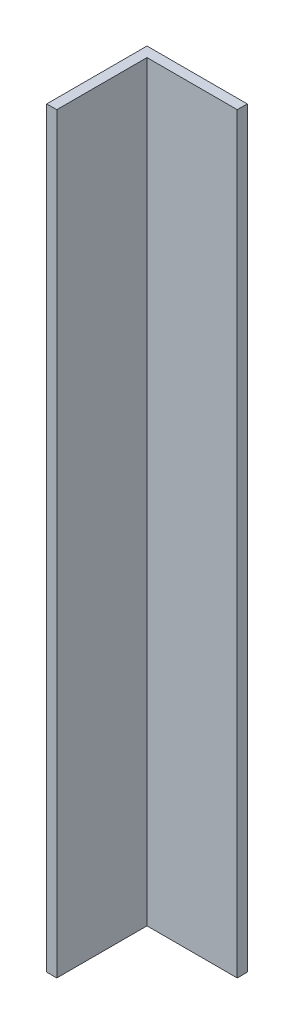
SolidWorks part; units mm, degrees
ref_plane "Front Plane" through (0, 0, 0) normal (0, 0, 1) x (1, 0, 0)
ref_plane "Top Plane" through (0, 0, 0) normal (0, 1, 0) x (1, 0, 0)
ref_plane "Right Plane" through (0, 0, 0) normal (1, 0, 0) x (0, 0, -1)
sketch "Sketch1" plane through (0, 0, 0) normal (0, 1, 0) x (1, 0, 0)
  line L0 (-4.6716, 238.0154) -> (-24.6716, 238.0154)
  line L1 (-24.6716, 238.0154) -> (-24.6716, 218.0154)
  line L2 (-4.6716, 236.0154) -> (-22.6716, 236.0154)
  line L3 (-22.6716, 236.0154) -> (-22.6716, 218.0154)
  line L4 (-4.6716, 238.0154) -> (-4.6716, 236.0154)
  line L5 (-22.6716, 218.0154) -> (-24.6716, 218.0154)
  dimension "D1" = 20
  dimension "D2" = 20
  dimension "D3" = 2
extrude "Boss-Extrude1" add sketch "Sketch1" along normal blind 150
